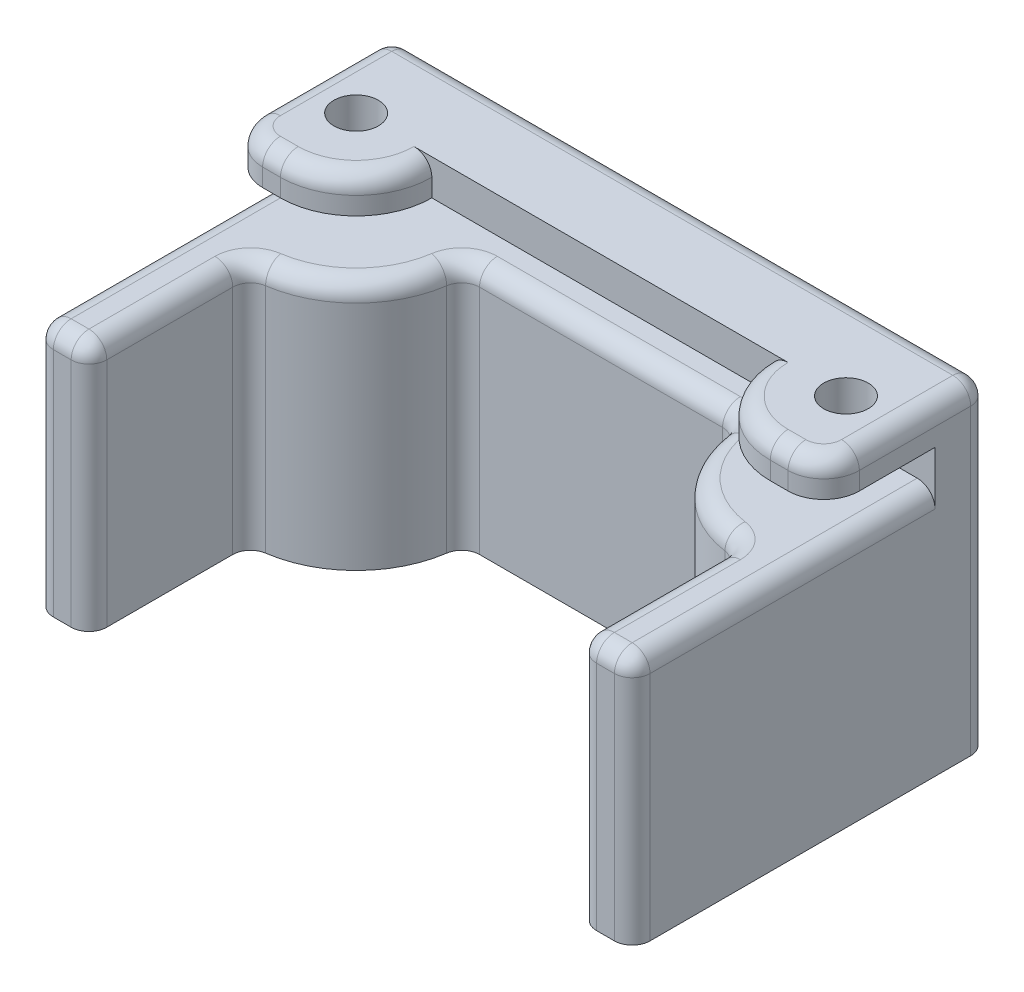
SolidWorks part; units mm, degrees
ref_plane "Front Plane" through (0, 0, 0) normal (0, 0, 1) x (1, 0, 0)
ref_plane "Top Plane" through (0, 0, 0) normal (0, 1, 0) x (1, 0, 0)
ref_plane "Right Plane" through (0, 0, 0) normal (1, 0, 0) x (0, 0, -1)
sketch "Sketch2" plane through (0, 0, 0) normal (0, 1, 0) x (1, 0, 0)
  line L0 (-16.75, -14) -> (-16.75, 4)
  line L1 (-15.75, 5) -> (15.75, 5)
  line L2 (-6.8218, 0) -> (6.8218, 0)
  line L3 (13.75, -6.9282) -> (13.75, -14)
  line L4 (14.75, -15) -> (15.75, -15)
  line L5 (-13.75, -6.9282) -> (-13.75, -14)
  line L6 (-14.75, -15) -> (-15.75, -15)
  line L7 (16.75, -14) -> (16.75, 4)
  arc A0 (-12.8929, -5.9385) -> (-7.8115, -0.8571) centre (-13.75, 0) ccw
  arc A1 (7.8115, -0.8571) -> (12.8929, -5.9385) centre (13.75, 0) ccw
  arc A2 (-13.75, -14) -> (-14.75, -15) centre (-14.75, -14) cw
  arc A3 (13.75, -14) -> (14.75, -15) centre (14.75, -14) ccw
  arc A4 (6.8218, 0) -> (7.8115, -0.8571) centre (6.8218, -1) cw
  arc A5 (13.75, -6.9282) -> (12.8929, -5.9385) centre (12.75, -6.9282) ccw
  arc A6 (-13.75, -6.9282) -> (-12.8929, -5.9385) centre (-12.75, -6.9282) cw
  arc A7 (-6.8218, 0) -> (-7.8115, -0.8571) centre (-6.8218, -1) ccw
  arc A8 (15.75, -15) -> (16.75, -14) centre (15.75, -14) ccw
  arc A9 (15.75, 5) -> (16.75, 4) centre (15.75, 4) cw
  arc A10 (-15.75, 5) -> (-16.75, 4) centre (-15.75, 4) ccw
  arc A11 (-15.75, -15) -> (-16.75, -14) centre (-15.75, -14) cw
  point P32 (0, 0)
  dimension "D1" = 6
  dimension "D3" = 1
  dimension "D4" = 1
  dimension "D5" = 15
  dimension "D8" = 27.5
  dimension "D2" = 27.5
  dimension "D6" = 3
  dimension "D7" = 5
  dimension "D9" = 13.75
extrude "Main body" add sketch "Sketch2" along normal blind 14
sketch "Sketch3" plane through (0, 14, 0) normal (0, 1, 0) x (1, 0, 0)
  line L0 (16.75, -14) -> (16.75, 4) construction
  line L1 (-16.75, 4) -> (-16.75, -14) construction
  line L2 (15.75, 5) -> (-15.75, 5) construction
  line L3 (16.75, 2) -> (16.75, 4)
  line L4 (-16.75, 4) -> (-16.75, 2)
  line L5 (15.75, 5) -> (-15.75, 5)
  line L6 (-16.75, 2) -> (16.75, 2)
  line L7 (-6.8218, 0) -> (6.8218, 0) construction
  arc A0 (16.75, 4) -> (15.75, 5) centre (15.75, 4) ccw construction
  arc A1 (-15.75, 5) -> (-16.75, 4) centre (-15.75, 4) ccw construction
  arc A2 (16.75, 4) -> (15.75, 5) centre (15.75, 4) ccw
  arc A3 (-15.75, 5) -> (-16.75, 4) centre (-15.75, 4) ccw
  dimension "D1" = 2
extrude "Extension for top flange" add sketch "Sketch3" along normal blind 2
sketch "Sketch4" plane through (0, 16, 0) normal (0, 1, 0) x (1, 0, 0)
  line L0 (16.75, -14) -> (16.75, 2) construction
  line L1 (16.75, 2) -> (16.75, 4) construction
  line L2 (15.75, 5) -> (-15.75, 5) construction
  line L3 (-16.75, 4) -> (-16.75, 2) construction
  line L4 (-16.75, 2) -> (-16.75, -14) construction
  line L5 (16.75, -2.25) -> (16.75, 2)
  line L6 (16.75, 2) -> (16.75, 4)
  line L7 (15.75, 5) -> (-15.75, 5)
  line L8 (-16.75, 4) -> (-16.75, 2)
  line L9 (-16.75, 2) -> (-16.75, -2.25)
  line L10 (-9.5, 0) -> (9.5, 0)
  line L11 (13.75, -4.25) -> (14.75, -4.25)
  line L12 (-13.75, -4.25) -> (-14.75, -4.25)
  arc A0 (16.75, 4) -> (15.75, 5) centre (15.75, 4) ccw construction
  arc A1 (-15.75, 5) -> (-16.75, 4) centre (-15.75, 4) ccw construction
  arc A2 (16.75, 4) -> (15.75, 5) centre (15.75, 4) ccw
  arc A3 (-15.75, 5) -> (-16.75, 4) centre (-15.75, 4) ccw
  circle A4 centre (-13.75, 0) radius 1.25
  circle A5 centre (13.75, 0) radius 1.25
  arc A6 (-12.8929, -5.9385) -> (-7.8115, -0.8571) centre (-13.75, 0) ccw construction
  arc A7 (7.8115, -0.8571) -> (12.8929, -5.9385) centre (13.75, 0) ccw construction
  arc A8 (9.5, 0) -> (13.75, -4.25) centre (13.75, 0) ccw
  arc A9 (-13.75, -4.25) -> (-9.5, 0) centre (-13.75, 0) ccw
  circle A10 centre (13.75, 0) radius 4.25 construction
  circle A11 centre (-13.75, 0) radius 4.25 construction
  arc A12 (14.75, -4.25) -> (16.75, -2.25) centre (14.75, -2.25) ccw
  arc A13 (-14.75, -4.25) -> (-16.75, -2.25) centre (-14.75, -2.25) cw
  dimension "D1" = 2.5
  dimension "D3" = 2
  dimension "D2" = 3
extrude "Top camera flange" add sketch "Sketch4" along normal blind 2
sketch "Sketch5" plane through (0, 14, 0) normal (0, 1, 0) x (1, 0, 0)
  circle A0 centre (-13.75, 0) radius 1
  circle A1 centre (13.75, 0) radius 1
  dimension "D1" = 2
extrude "M2 screwhole" cut sketch "Sketch5" against normal through all both and the other way through all
fillet "Fillet1" radius 1 28 edges at (10.7448, 18, 3.0052) (14.25, 18, 4.25) (16.1642, 18, 3.6642) (16.75, 18, -0.875) (16.4571, 18, -4.7071) (-10.7448, 18, 3.0052) (-14.25, 18, 4.25) (-16.1642, 18, 3.6642) (-16.75, 18, -0.875) (-16.4571, 18, -4.7071) (0, 18, -5) (-16.75, 14, 6) (-16.4571, 14, 14.7071) (-15.25, 14, 15) (-14.0429, 14, 14.7071) (-13.75, 14, 10.4641) (-13.5059, 14, 6.2735) (-9.5074, 14, 4.2426) (-7.4765, 14, 0.2441) (16.75, 14, 6) (16.4571, 14, 14.7071) (15.25, 14, 15) (14.0429, 14, 14.7071) (13.75, 14, 10.4641) (13.5059, 14, 6.2735) (9.5074, 14, 4.2426) (7.4765, 14, 0.2441) (0, 14, 0)
